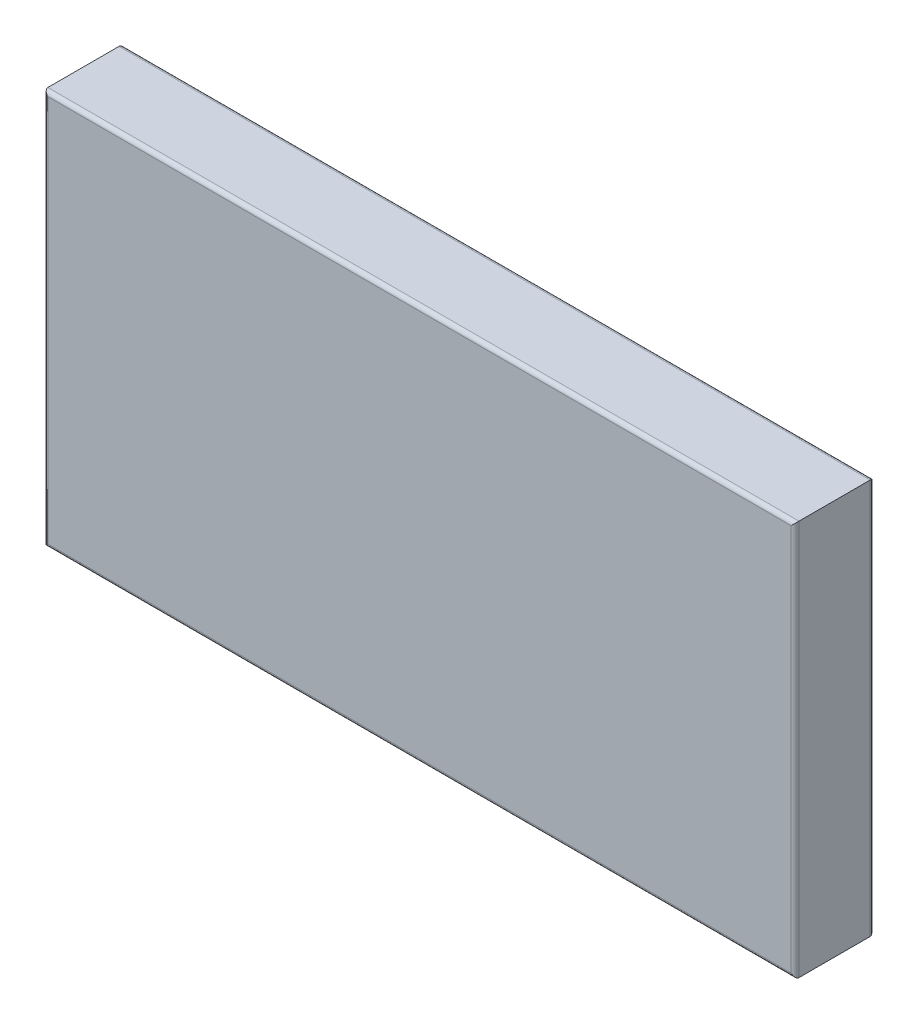
SolidWorks part; units mm, degrees
ref_plane "Front Plane" through (0, 0, 0) normal (0, 0, 1) x (1, 0, 0)
ref_plane "Top Plane" through (0, 0, 0) normal (0, 1, 0) x (1, 0, 0)
ref_plane "Right Plane" through (0, 0, 0) normal (1, 0, 0) x (0, 0, -1)
sketch "Sketch1" plane through (0, 0, 0) normal (0, 0, 1) x (1, 0, 0)
  line L1 (0, 0) -> (190, 0)
  line L2 (0, 0) -> (0, 100)
  line L3 (0, 100) -> (190, 100)
  line L4 (190, 0) -> (190, 100)
  dimension "D1" = 190
  dimension "D2" = 100
extrude "Boss-Extrude1" add sketch "Sketch1" along normal blind 20
fillet "Fillet1" radius 1 8 edges at (0, 50, 0) (95, 100, 0) (190, 50, 0) (95, 0, 0) (0, 50, 20) (95, 100, 20) (190, 50, 20) (95, 0, 20)
scale "Scale1" scale about origin uniform scaling yes scale factor 10
